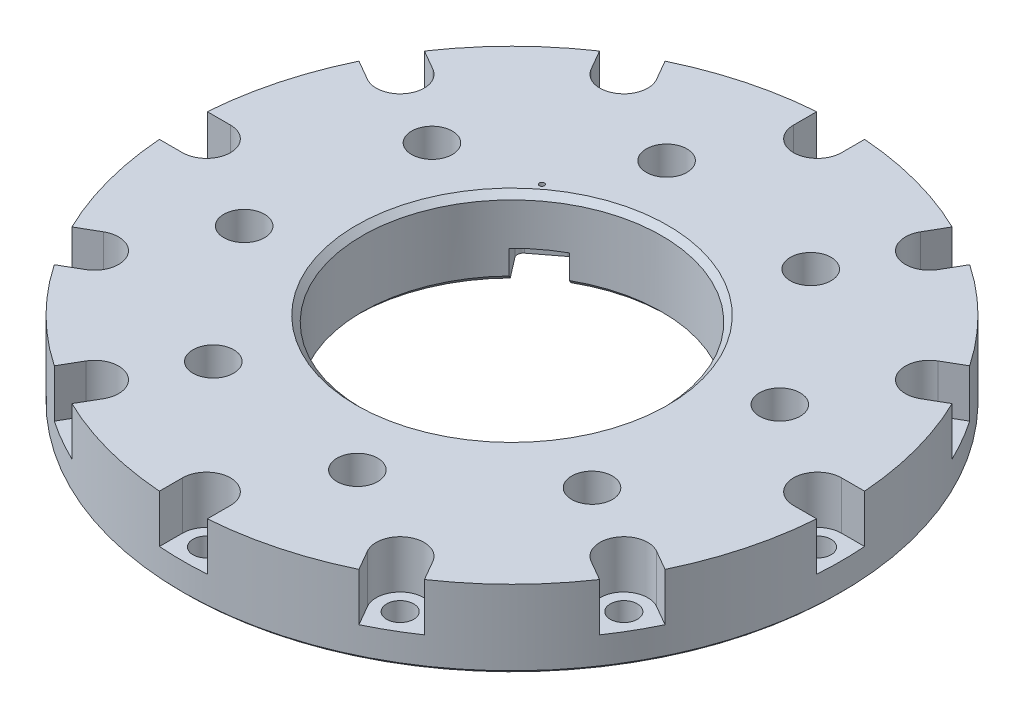
SolidWorks part; units mm, degrees
material "7075-T6"
ref_plane "前视" through (0, 0, 0) normal (0, 0, 1) x (1, 0, 0)
ref_plane "上视" through (0, 0, 0) normal (0, 1, 0) x (1, 0, 0)
ref_plane "右视" through (0, 0, 0) normal (1, 0, 0) x (0, 0, -1)
sketch "草图1" plane through (0, 0, 0) normal (0, 0, 1) x (1, 0, 0)
  line L0 (0, 0) -> (0, -150.2913) construction
  line L3 (-55, 0) -> (-55, -13)
  line L4 (-55, -13) -> (-25, -13)
  line L5 (-25, -13) -> (-25, 0)
  line L6 (-25, 0) -> (-55, 0)
  dimension "D1" = 50
  dimension "D2" = 110
  dimension "D5" = 13
revolve "旋转1" add sketch "草图1" angle 360 about L0
sketch "草图2" plane through (0, 0, 0) normal (0, 1, 0) x (1, 0, 0)
  line L0 (0, 65.6258) -> (0, 51) construction
  line L1 (4, 65.6258) -> (4, 51)
  line L2 (-4, 65.6258) -> (-4, 51)
  arc A1 (4, 65.6258) -> (-4, 65.6258) centre (0, 65.6258) ccw
  arc A2 (-4, 51) -> (4, 51) centre (0, 51) ccw
  point P6 (0, 58.3129)
  dimension "D1" = 4
  dimension "D2" = 51
extrude "切除-拉伸1" cut sketch "草图2" against normal blind 8
sketch "草图3" plane through (0, -8, 0) normal (0, 1, 0) x (1, 0, 0)
  line L0 (0, 51) -> (0, 0) construction
  circle A0 centre (0, 51) radius 2.25
  dimension "D2" = 4.5
  dimension "D1" = 51
extrude "切除-拉伸2" cut sketch "草图3" against normal through all
pattern_circular "阵列(圆周)1" count 12 over 360 about axis through (0, 0, 0) along (0, 1, 0) of "切除-拉伸2", "切除-拉伸1"
chamfer "倒角1" distance 1 angle 45 2 edges at (0, -13, 25) (0, 0, 25)
chamfer "倒角2" distance 0.5 angle 45 1 edges at (0, -13, 55)
hole_wizard "M8 螺纹孔2" positions "草图6" profile "草图7" tap size "M8" standard "GB" end condition through all
sketch "草图6" plane through (0, 0, 0) normal (0, 1, 0) x (1, 0, 0)
  line L0 (35.2563, 9.4469) -> (0, 0) construction
  line L1 (0, 0) -> (63.8955, 0) construction
  point P0 (35.2563, 9.4469)
  dimension "D1" = 15
  dimension "D2" = 36.5
sketch "草图7" plane through (35.2563, 0, -9.4469) normal (1, 0, 0) x (0, 0, 1)
  line L0 (0, 0) -> (0, 13)
  line L1 (0, 13) -> (3.4, 13)
  line L2 (3.4, 13) -> (3.4, 0)
  line L5 (3.4, 0) -> (0, 0)
  line L11 (0, -6.35) -> (0, 107.95) construction
  dimension "通孔螺纹孔钻头直径" = 6.8
  dimension "通孔螺纹孔钻头深度" = 13
cosmetic thread "孔螺蚊线1" parameters "D2"=8
pattern_circular "阵列(圆周)2" count 8 over 360 about axis through (0, 0, 0) along (0, 1, 0) of "M8 螺纹孔2"
sketch "草图8" plane through (0, -13, 0) normal (0, -1, 0) x (1, 0, 0)
  line L0 (-21.7277, -22.4024) -> (-14.4225, -12.8822)
  line L1 (-21.7277, -22.4024) -> (-16.0155, -26.7855)
  line L2 (-14.4225, -12.8822) -> (-8.7104, -17.2653)
  line L3 (-16.0155, -26.7855) -> (-8.7104, -17.2653)
  line L4 (-21.7277, -22.4024) -> (-8.7104, -17.2653) construction
  line L5 (-14.4225, -12.8822) -> (-16.0155, -26.7855) construction
  line L6 (-15.219, -19.8338) -> (0, 0) construction
  line L7 (0, -51) -> (0, 0) construction
  line L8 (0, 0) -> (-31.6099, -18.25) construction
  line L9 (-9.4469, -35.2563) -> (0, 0) construction
  circle A0 centre (0, 0) radius 25 construction
  point P1 (-15.219, -19.8338)
  dimension "D1" = 37.5
  dimension "D2" = 7.2
  dimension "D3" = 12
extrude "切除-拉伸3" cut sketch "草图8" against normal blind 5
fillet "圆角1" radius 1 2 edges at (-16.0155, -10.5, -26.7855) (-21.7277, -10.5, -22.4024)
hole_wizard "M3 螺纹孔1" positions "草图9" profile "草图10" tap size "M3" standard "GB"
sketch "草图9" plane through (0, -8, 0) normal (0, -1, 0) x (-1, 0, 0)
  line L0 (0, 66.9318) -> (0, 0) construction
  line L1 (0, 0) -> (16.4366, 21.4205) construction
  point P0 (16.4366, 21.4205)
  dimension "D1" = 37.5
  dimension "D2" = 27
cosmetic thread "孔螺蚊线2" parameters "D1"=6, "D2"=3
sketch "草图10" plane through (-16.4366, -8, -21.4205) normal (1, 0, 0) x (0, 0, -1)
  line L0 (0, 0) -> (0, 8.2511)
  line L1 (0, 8.2511) -> (1.25, 7.5)
  line L2 (1.25, 7.5) -> (1.25, 0)
  line L5 (1.25, 0) -> (0, 0)
  line L10 (0, 8.2511) -> (-1.25, 7.5) construction
  line L11 (0, -6.35) -> (0, 107.95) construction
  dimension "螺纹孔钻头直径" = 2.5
  dimension "螺纹孔钻头深度" = 7.5
  dimension "导头角度" = 118
